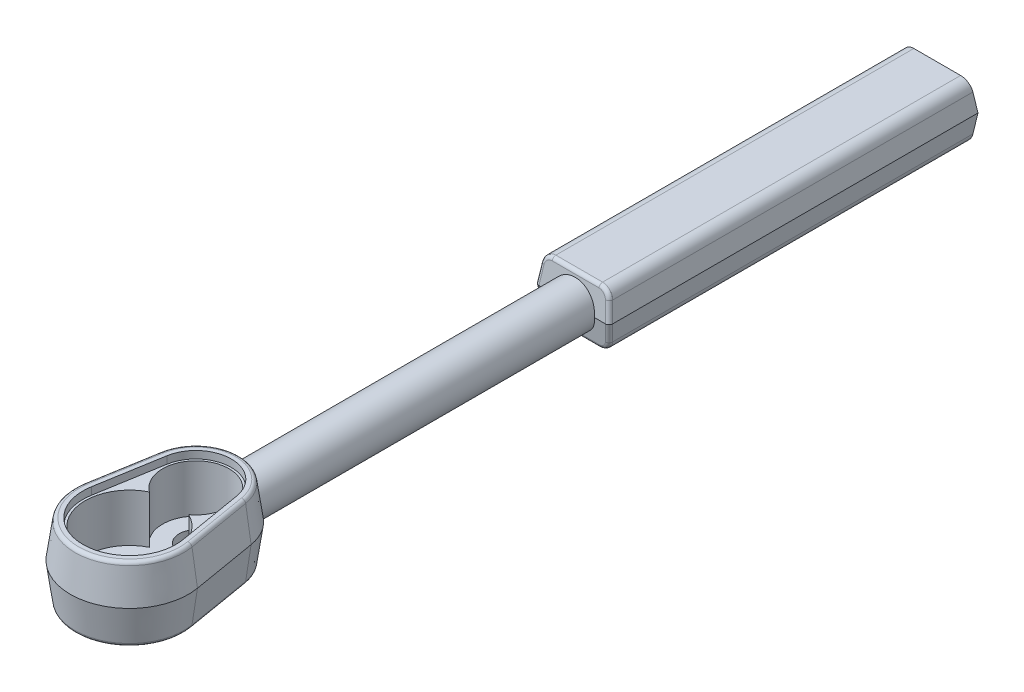
SolidWorks part; units mm, degrees
ref_plane "Front Plane" through (0, 0, 0) normal (0, 0, 1) x (1, 0, 0)
ref_plane "Top Plane" through (0, 0, 0) normal (0, 1, 0) x (1, 0, 0)
ref_plane "Right Plane" through (0, 0, 0) normal (1, 0, 0) x (0, 0, -1)
sketch "Sketch1" plane through (0, 0, 0) normal (0, 1, 0) x (1, 0, 0)
  line L0 (0, 0) -> (0, 220)
  line L1 (-10, 220) -> (10, 220)
  line L2 (10, 220) -> (10, 120)
  line L3 (-10, 220) -> (-10, 120)
  line L4 (10, 120) -> (-10, 120)
  dimension "D1" = 10
  dimension "D2" = 220
  dimension "D3" = 120
extrude "Handle" add sketch "Sketch1" along normal mid plane 15 draft 8 contours L2 L4 L3 L1
sketch "Sketch2" plane through (0, 0, 0) normal (0, 0, 1) x (1, 0, 0)
  circle A0 centre (0, 0) radius 6
  dimension "D1" = 12
extrude "Transition" add sketch "Sketch2" against normal up to next
sketch "Sketch3" plane through (0, 0, 0) normal (0, 1, 0) x (1, 0, 0)
  line L0 (0, 0) -> (0, 18)
  line L1 (12.8182, 20.1667) -> (15.7762, 2.6667)
  line L2 (-12.8182, 20.1667) -> (-15.7762, 2.6667)
  arc A0 (15.7762, 2.6667) -> (-15.7762, 2.6667) centre (0, 0) cw
  arc A1 (-12.8182, 20.1667) -> (12.8182, 20.1667) centre (0, 18) cw
  dimension "D1" = 16
  dimension "D3" = 13
  dimension "D2" = 18
extrude "Boss-Extrude3" add sketch "Sketch3" along normal mid plane 20 draft 8
sketch "Sketch4" plane through (0, 10, 0) normal (0, 1, 0) x (1, 0, 0)
  line L4 (-9.4604, 19.5991) -> (-12.4184, 2.0991)
  line L5 (12.4184, 2.0991) -> (9.4604, 19.5991)
  line L6 (-9.4604, 19.5991) -> (-12.4184, 2.0991)
  line L7 (12.4184, 2.0991) -> (9.4604, 19.5991)
  arc A4 (9.4604, 19.5991) -> (-9.4604, 19.5991) centre (0, 18) ccw
  arc A5 (-12.4184, 2.0991) -> (12.4184, 2.0991) centre (0, 0) ccw
  arc A6 (9.4604, 19.5991) -> (-9.4604, 19.5991) centre (0, 18) ccw
  arc A7 (-12.4184, 2.0991) -> (12.4184, 2.0991) centre (0, 0) ccw
  dimension "D1" = 2
extrude "Recess" cut sketch "Sketch4" against normal blind 2
sketch "Sketch5" plane through (0, 8, 0) normal (0, 1, 0) x (1, 0, 0)
  arc A0 (-5.3327, 10.75) -> (5.3327, 10.75) centre (0, 0) ccw
  arc A1 (5.3327, 10.75) -> (-5.3327, 10.75) centre (0, 18) ccw
  arc A2 (-14.3905, 2.4324) -> (14.3905, 2.4324) centre (0, 0) ccw construction
  arc A3 (11.4324, 19.9324) -> (-11.4324, 19.9324) centre (0, 18) ccw construction
  dimension "D1" = 24
  dimension "D2" = 18
extrude "Offset" cut sketch "Sketch5" against normal offset from surface (13 mm away) 5 contours A1 A0 up to face at (0, -10, -9.3412)
sketch "Sketch7" plane through (0, -5, 0) normal (0, 1, 0) x (1, 0, 0)
  circle A0 centre (0, 18) radius 4.5
  arc A2 (5.3327, 10.75) -> (-5.3327, 10.75) centre (0, 18) ccw construction
  dimension "D1" = 9
extrude "WheelHole" cut sketch "Sketch7" against normal through all contours A0
sketch "Sketch8" plane through (0, -5, 0) normal (0, 1, 0) x (1, 0, 0)
  circle A0 centre (0, 0) radius 4.5
  arc A3 (-5.3327, 10.75) -> (5.3327, 10.75) centre (0, 0) ccw construction
  dimension "D1" = 9
extrude "Cut-Extrude4" cut sketch "Sketch8" against normal through all contours A0
fillet "Handle Fillet" radius 3 4 edges at (8.9459, 7.5, -170) (-8.9459, 7.5, -170) (-8.9459, -7.5, -170) (8.9459, -7.5, -170)
fillet "Fillet2" radius 1 10 edges at (0, 7.5, -121.0541) (9.6544, 2.4588, -120.3456) (-9.6544, 2.4588, -120.3456) (8.3063, 6.7641, -120.9506) (-8.3063, 6.7641, -120.9506) (-9.6544, -2.4588, -120.3456) (0, -7.5, -121.0541) (9.6544, -2.4588, -120.3456) (8.3063, -6.7641, -120.9506) (-8.3063, -6.7641, -120.9506)
fillet "Fillet3" radius 1 8 edges at (0, -10, -29.5946) (12.9114, -10, -11.1824) (-12.9114, -10, -11.1824) (0, -10, 14.5946) (12.9114, 10, -11.1824) (0, 10, -29.5946) (-12.9114, 10, -11.1824) (0, 10, 14.5946)
